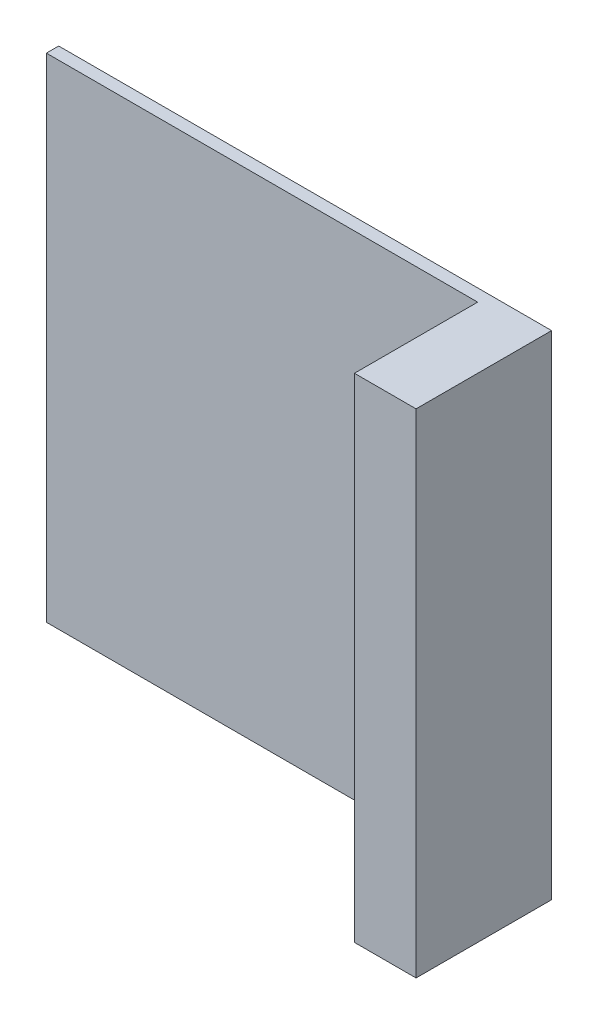
SolidWorks part; units mm, degrees
ref_plane "Front Plane" through (0, 0, 0) normal (0, 0, 1) x (1, 0, 0)
ref_plane "Top Plane" through (0, 0, 0) normal (0, 1, 0) x (1, 0, 0)
ref_plane "Right Plane" through (0, 0, 0) normal (1, 0, 0) x (0, 0, -1)
sketch "Sketch1" plane through (0, 0, 0) normal (0, 0, 1) x (1, 0, 0)
  line L1 (-68.947, 368.5997) -> (331.053, 368.5997)
  line L2 (-68.947, 368.5997) -> (-68.947, -31.4003)
  line L3 (-68.947, -31.4003) -> (331.053, -31.4003)
  line L4 (331.053, 368.5997) -> (331.053, -31.4003)
extrude "Boss-Extrude1" add sketch "Sketch1" along normal blind 10
sketch "Sketch2" plane through (0, 0, 10) normal (0, 0, 1) x (1, 0, 0)
  line L0 (-68.947, -31.4003) -> (331.053, -31.4003) construction
  line L1 (331.053, 368.5997) -> (281.053, 368.5997)
  line L2 (331.053, 368.5997) -> (331.053, -31.4003)
  line L3 (331.053, -31.4003) -> (281.053, -31.4003)
  line L4 (281.053, 368.5997) -> (281.053, -31.4003)
extrude "Boss-Extrude2" add sketch "Sketch2" along normal blind 100
